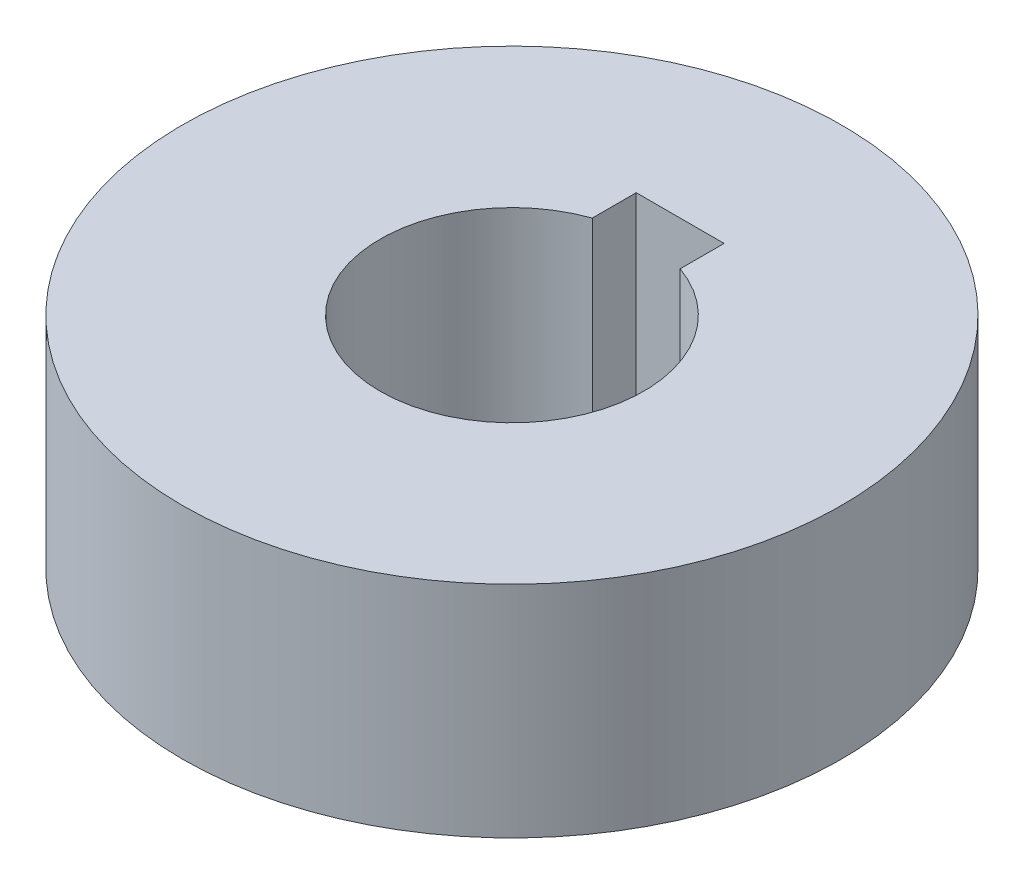
SolidWorks part; units mm, degrees
ref_plane "Front Plane" through (0, 0, 0) normal (0, 0, 1) x (1, 0, 0)
ref_plane "Top Plane" through (0, 0, 0) normal (0, 1, 0) x (1, 0, 0)
ref_plane "Right Plane" through (0, 0, 0) normal (1, 0, 0) x (0, 0, -1)
sketch "Sketch1" plane through (0, 0, 0) normal (0, 1, 0) x (1, 0, 0)
  circle A0 centre (0, 0) radius 15
  circle A1 centre (0, 0) radius 6
  dimension "D1" = 12
  dimension "D2" = 30
extrude "Boss-Extrude1" add sketch "Sketch1" along normal blind 10
sketch "Sketch2" plane through (0, 10, 0) normal (0, 1, 0) x (1, 0, 0)
  line L0 (0, 0) -> (0, 6) construction
  line L1 (0, 6) -> (0, 7.6569) construction
  line L2 (2, 7.6569) -> (-2, 7.6569)
  line L3 (-2, 7.6569) -> (-2, 5.6569)
  line L4 (2, 7.6569) -> (2, 5.6569)
  circle A0 centre (0, 0) radius 6 construction
  circle A1 centre (0, 0) radius 6
  circle M6 centre (0, 0) radius 6
  dimension "D1" = 2
  dimension "D2" = 2
extrude "Cut-Extrude1" cut sketch "Sketch2" against normal through all contours L4 L2 L3 M6
equation "\"shaft-diameter\" =20mm"
equation "\"key-length\"=12mm"
equation "\"key-width\"=4mm"
equation "\"flippershaft-wormgear-diameter\" = 35mm"
equation "\"shaft-ring-groove-depth\"=0.5mm"
equation "\"shaft-ring-groove-width\" = 1.3mm"
equation "\"mini-shaft-diameter\" = 12mm"
equation "\"D1@Sketch1\"=\"mini-shaft-diameter\""
equation "\"D2@Sketch2\"=\"key-width\"/2"
